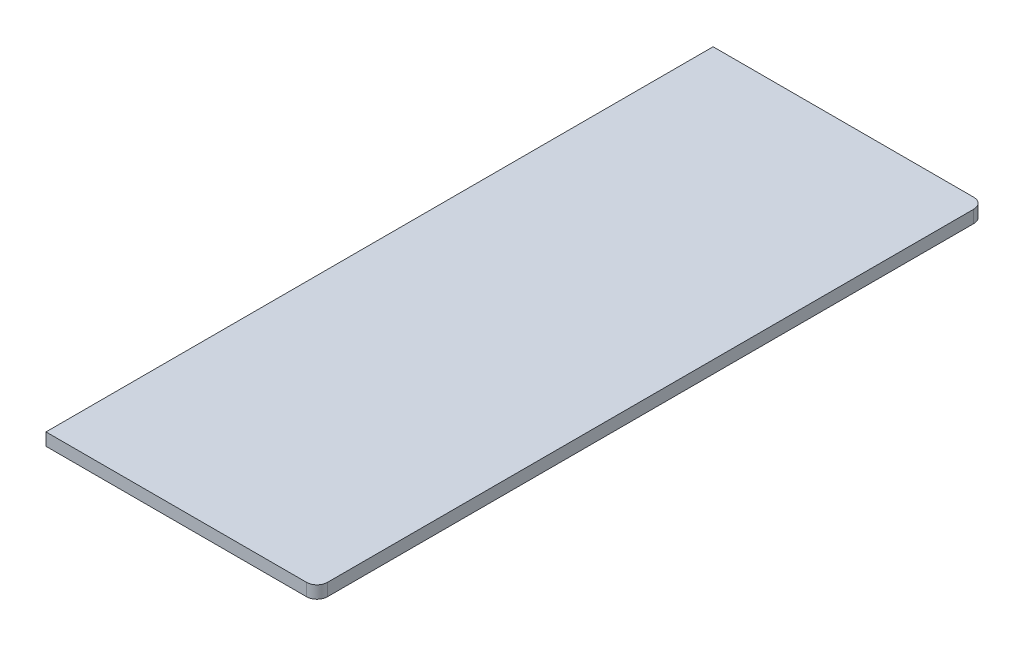
SolidWorks part; units mm, degrees
ref_plane "Front Plane" through (0, 0, 0) normal (0, 0, 1) x (1, 0, 0)
ref_plane "Top Plane" through (0, 0, 0) normal (0, 1, 0) x (1, 0, 0)
ref_plane "Right Plane" through (0, 0, 0) normal (1, 0, 0) x (0, 0, -1)
sketch "Sketch1" plane through (0, 0, 0) normal (0, 1, 0) x (1, 0, 0)
  line L0 (0, 0) -> (0, -320)
  line L1 (0, -320) -> (130, -320)
  line L2 (130, -320) -> (130, 0)
  line L3 (130, 0) -> (0, 0)
  dimension "D1" = 130
  dimension "D2" = 320
extrude "Boss-Extrude1" add sketch "Sketch1" along normal blind 6
fillet "Fillet1" radius 5 2 edges at (130, 3, 0) (130, 3, 320)
